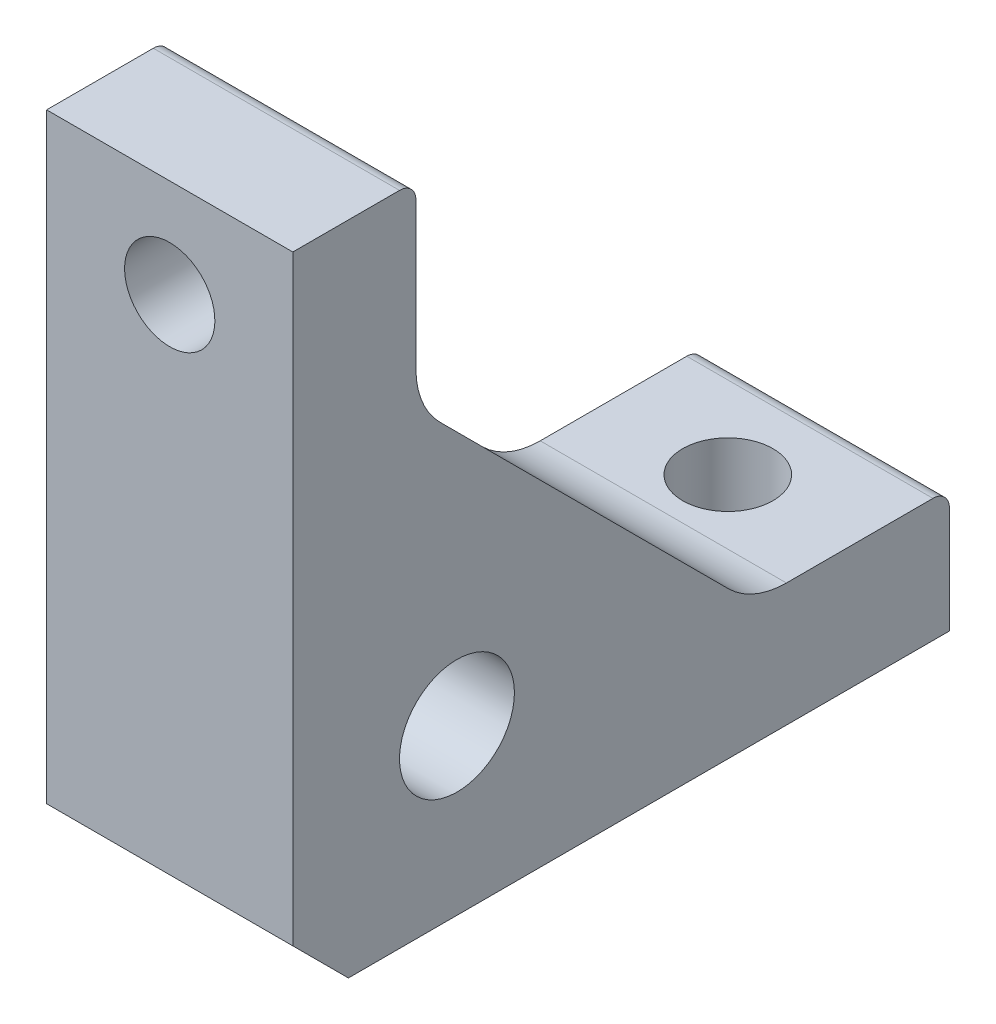
SolidWorks part; units mm, degrees
ref_plane "Front Plane" through (0, 0, 0) normal (0, 0, 1) x (1, 0, 0)
ref_plane "Top Plane" through (0, 0, 0) normal (0, 1, 0) x (1, 0, 0)
ref_plane "Right Plane" through (0, 0, 0) normal (1, 0, 0) x (0, 0, -1)
sketch "Sketch2" plane through (0, 0, 0) normal (1, 0, 0) x (0, 0, -1)
  line L0 (0, 3.3865) -> (0, 40)
  line L1 (0, 40) -> (7.5, 40)
  line L2 (7.5, 40) -> (7.5, 28)
  line L3 (7.5, 28) -> (28, 7.5)
  line L4 (28, 7.5) -> (40, 7.5)
  line L5 (40, 7.5) -> (40, 0)
  line L6 (40, 0) -> (3.3865, 0)
  line L7 (0, 3.3865) -> (3.3865, 0)
  circle A0 centre (10, 10) radius 3.5
  dimension "D1" = 7
  dimension "D2" = 10
  dimension "D3" = 10
  dimension "D4" = 40
  dimension "D5" = 40
  dimension "D6" = 7.5
  dimension "D7" = 7.5
  dimension "D8" = 135
  dimension "D9" = 12
extrude "Boss-Extrude1" add sketch "Sketch2" along normal blind 15
sketch "Sketch3" plane through (0, 7.5, 0) normal (0, 1, 0) x (1, 0, 0)
  line L0 (0, 40) -> (0, 28) construction
  line L1 (15, 40) -> (0, 40) construction
  circle A0 centre (7.5, 34) radius 2.75
  dimension "D1" = 5.5
  dimension "D2" = 7.5
  dimension "D3" = 6
extrude "Cut-Extrude1" cut sketch "Sketch3" against normal blind 15 contours A0
sketch "Sketch4" plane through (0, 0, -7.5) normal (0, 0, -1) x (-1, 0, 0)
  line L0 (0, 28) -> (0, 40) construction
  line L1 (-15, 40) -> (0, 40) construction
  circle A0 centre (-7.5, 34) radius 2.75
  dimension "D1" = 5.5
  dimension "D2" = 7.5
  dimension "D3" = 6
extrude "Cut-Extrude2" cut sketch "Sketch4" against normal blind 15
fillet "Fillet1" radius 5 2 edges at (7.5, 7.5, -28) (7.5, 28, -7.5)
fillet "Fillet2" radius 1 2 edges at (7.5, 7.5, -40) (7.5, 40, -7.5)
